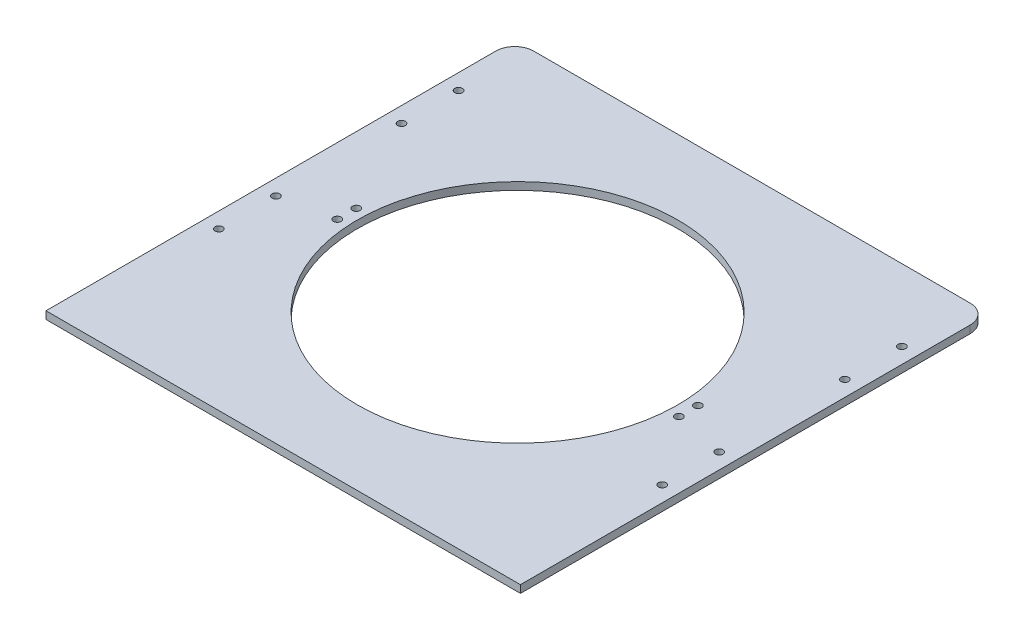
SolidWorks part; units mm, degrees
material "Medium density fiberboard, parallel to board"
ref_plane "Alzado" through (0, 0, 0) normal (0, 0, 1) x (1, 0, 0)
ref_plane "Planta" through (0, 0, 0) normal (0, 1, 0) x (1, 0, 0)
ref_plane "Vista lateral" through (0, 0, 0) normal (1, 0, 0) x (0, 0, -1)
sketch "Croquis1" plane through (0, 0, 0) normal (0, 1, 0) x (1, 0, 0)
  line L1 (-125, -123.5) -> (125, -123.5)
  line L2 (-125, -123.5) -> (-125, 113.5)
  line L3 (-115, 123.5) -> (115, 123.5)
  line L4 (125, -123.5) -> (125, 113.5)
  line L5 (-125, -123.5) -> (125, 123.5) construction
  line L6 (-125, 123.5) -> (125, -123.5) construction
  arc A0 (115, 123.5) -> (125, 113.5) centre (115, 113.5) cw
  arc A1 (-125, 113.5) -> (-115, 123.5) centre (-115, 113.5) cw
  point P0 (0, 0)
  dimension "D3" = 10
  dimension "D1" = 250
  dimension "D2" = 247
extrude "Saliente-Extruir1" add sketch "Croquis1" along normal blind 4
sketch "Croquis2" plane through (0, 4, 0) normal (0, 1, 0) x (1, 0, 0)
  line L0 (-125, 0) -> (125, 0) construction
  line L1 (-125, 113.5) -> (-125, -123.5) construction
  line L2 (125, -123.5) -> (125, 113.5) construction
  line L3 (0, 84.42) -> (0, -84.42) construction
  circle A0 centre (0, 0) radius 84.42
  circle A1 centre (-90, 5) radius 2
  circle A2 centre (-90, -5) radius 2
  circle A3 centre (90, -5) radius 2
  circle A4 centre (90, 5) radius 2
  dimension "D1" = 168.84
  dimension "D2" = 4
  dimension "D3" = 4
  dimension "D4" = 10
  dimension "D5" = 5
  dimension "D6" = 90
  dimension "D7" = 90
extrude "Cortar-Extruir1" cut sketch "Croquis2" against normal blind 4
sketch "Croquis3" plane through (0, 4, 0) normal (0, 1, 0) x (1, 0, 0)
  line L0 (115, 123.5) -> (-115, 123.5) construction
  line L1 (-125, 113.5) -> (-125, -123.5) construction
  line L2 (0, 33.527) -> (0, -33.527) construction
  circle A0 centre (-116.8, 85.7) radius 2
  circle A1 centre (-116.8, 55.65) radius 2
  circle A2 centre (-116.8, -10.55) radius 2
  circle A3 centre (-116.8, -40.6) radius 2
  circle A4 centre (116.8, -40.6) radius 2
  circle A5 centre (116.8, -10.55) radius 2
  circle A6 centre (116.8, 55.65) radius 2
  circle A7 centre (116.8, 85.7) radius 2
  point P15 (0, 0)
  dimension "D5" = 4
  dimension "D6" = 4
  dimension "D9" = 4
  dimension "D10" = 4
  dimension "D1" = 30.05
  dimension "D2" = 37.8
  dimension "D3" = 8.2
  dimension "D4" = 8.2
  dimension "D7" = 30.05
  dimension "D8" = 66.2
  dimension "D11" = 8.2
  dimension "D12" = 8.2
extrude "Cortar-Extruir2" cut sketch "Croquis3" against normal blind 10
